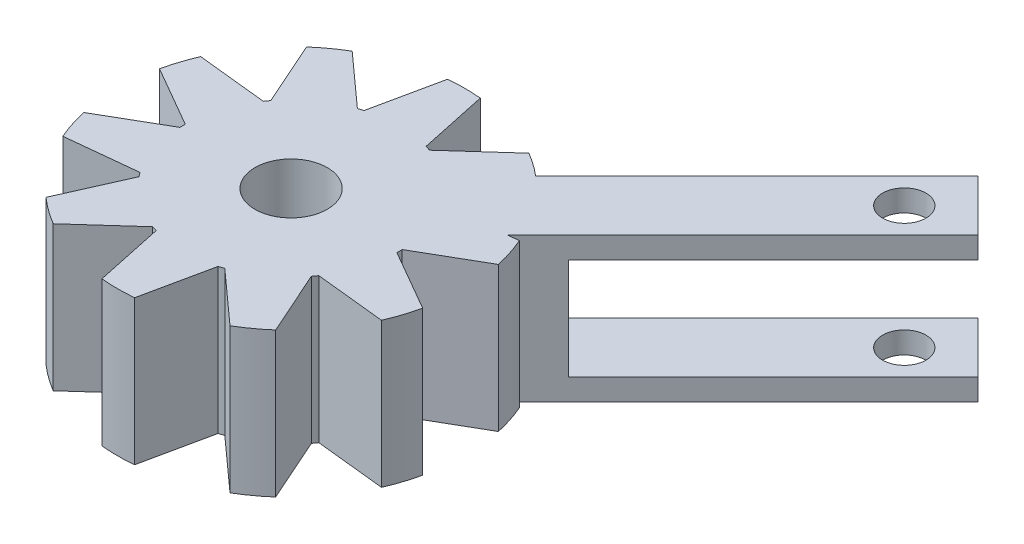
SolidWorks part; units mm, degrees
ref_plane "Front Plane" through (0, 0, 0) normal (0, 0, 1) x (1, 0, 0)
ref_plane "Top Plane" through (0, 0, 0) normal (0, 1, 0) x (1, 0, 0)
ref_plane "Right Plane" through (0, 0, 0) normal (1, 0, 0) x (0, 0, -1)
sketch "Sketch1" plane through (0, 0, 0) normal (0, 1, 0) x (1, 0, 0)
  line L0 (0, 0) -> (0, 13.746) construction
  line L1 (-1.57, 9.876) -> (1.57, 9.876)
  line L2 (1.1299, 11.9467) -> (2.1414, 7.1878)
  line L3 (-1.1299, 11.9467) -> (-2.1414, 7.1878)
  line L4 (7.9362, 9.001) -> (5.9573, 4.5564)
  line L5 (6.108, 10.3292) -> (2.4925, 7.0737)
  line L6 (11.7111, 2.6172) -> (7.4977, 0.1846)
  line L7 (11.0128, 4.7663) -> (6.1743, 4.2577)
  line L8 (11.0128, -4.7663) -> (6.1743, -4.2577)
  line L9 (11.7111, -2.6172) -> (7.4977, -0.1846)
  line L10 (6.108, -10.3292) -> (2.4925, -7.0737)
  line L11 (7.9362, -9.001) -> (5.9573, -4.5564)
  line L12 (-1.1299, -11.9467) -> (-2.1414, -7.1878)
  line L13 (1.1299, -11.9467) -> (2.1414, -7.1878)
  line L14 (-7.9362, -9.001) -> (-5.9573, -4.5564)
  line L15 (-6.108, -10.3292) -> (-2.4925, -7.0737)
  line L16 (-11.7111, -2.6172) -> (-7.4977, -0.1846)
  line L17 (-11.0128, -4.7663) -> (-6.1743, -4.2577)
  line L18 (-11.0128, 4.7663) -> (-6.1743, 4.2577)
  line L19 (-11.7111, 2.6172) -> (-7.4977, 0.1846)
  line L20 (-6.108, 10.3292) -> (-2.4925, 7.0737)
  line L21 (-7.9362, 9.001) -> (-5.9573, 4.5564)
  arc A0 (1.1299, 11.9467) -> (-1.1299, 11.9467) centre (0, 0) ccw
  arc A1 (-5.9573, 4.5564) -> (-6.1743, 4.2577) centre (0, 0) ccw
  circle A2 centre (0, 0) radius 10 construction
  arc A3 (7.9362, 9.001) -> (6.108, 10.3292) centre (0, 0) ccw
  arc A4 (11.7111, 2.6172) -> (11.0128, 4.7663) centre (0, 0) ccw
  arc A5 (11.0128, -4.7663) -> (11.7111, -2.6172) centre (0, 0) ccw
  arc A6 (6.108, -10.3292) -> (7.9362, -9.001) centre (0, 0) ccw
  arc A7 (-1.1299, -11.9467) -> (1.1299, -11.9467) centre (0, 0) ccw
  arc A8 (-7.9362, -9.001) -> (-6.108, -10.3292) centre (0, 0) ccw
  arc A9 (-11.7111, -2.6172) -> (-11.0128, -4.7663) centre (0, 0) ccw
  arc A10 (-11.0128, 4.7663) -> (-11.7111, 2.6172) centre (0, 0) ccw
  arc A11 (-6.108, 10.3292) -> (-7.9362, 9.001) centre (0, 0) ccw
  arc A12 (-7.4977, 0.1846) -> (-7.4977, -0.1846) centre (0, 0) ccw
  arc A13 (-6.1743, -4.2577) -> (-5.9573, -4.5564) centre (0, 0) ccw
  arc A14 (-2.4925, -7.0737) -> (-2.1414, -7.1878) centre (0, 0) ccw
  arc A15 (2.1414, -7.1878) -> (2.4925, -7.0737) centre (0, 0) ccw
  arc A16 (5.9573, -4.5564) -> (6.1743, -4.2577) centre (0, 0) ccw
  arc A17 (7.4977, -0.1846) -> (7.4977, 0.1846) centre (0, 0) ccw
  arc A18 (6.1743, 4.2577) -> (5.9573, 4.5564) centre (0, 0) ccw
  arc A19 (2.4925, 7.0737) -> (2.1414, 7.1878) centre (0, 0) ccw
  arc A20 (-2.1414, 7.1878) -> (-2.4925, 7.0737) centre (0, 0) ccw
  circle A21 centre (0, 0) radius 2.5
  point P50 (0, 0)
  dimension "D1" = 24
  dimension "D2" = 15
  dimension "D3" = 20
  dimension "D7" = 5
  dimension "D4" = 3.14
  dimension "D5" = 12
  dimension "D6" = 10
extrude "Boss-Extrude1" add sketch "Sketch1" along normal blind 10 contours L3 A20 L20 A11 L21 A1 L18 A10 L19 A12 L16 A9 L17 A13 L14 A8 L15 A14 L12 A7 L13 A15 L10 A6 L11 A16 L8 A5 L9 A17 L6 A4 L7 A18 L4 A3 L5 A19 L2 L1 A21 | L2 A0 L3 L1
sketch "Sketch2" plane through (0, 10, 0) normal (0, 1, 0) x (1, 0, 0)
  line L0 (1.7815, 3.2633) -> (22.9947, 24.4765)
  line L1 (22.9947, 24.4765) -> (26.5302, 20.9409)
  line L2 (26.5302, 20.9409) -> (5.317, -0.2723)
  line L3 (5.317, -0.2723) -> (1.7815, 3.2633)
  line L4 (3.5493, 1.4955) -> (29.0706, 27.0168) construction
  line L5 (0, 0) -> (27.6513, 0) construction
  dimension "D1" = 5
  dimension "D2" = 30
  dimension "D3" = 45
extrude "Boss-Extrude2" add sketch "Sketch2" against normal blind 10
sketch "Sketch3" plane through (0, 10, 0) normal (0, 1, 0) x (1, 0, 0)
  line L1 (10.2784, 4.6891) -> (26.5302, 20.9409) construction
  circle A0 centre (22.2152, 20.1615) radius 1.5
  dimension "D3" = 3
  dimension "D1" = 30
  dimension "D2" = 2.5
extrude "Cut-Extrude1" cut sketch "Sketch3" against normal blind 55
sketch "Sketch4" plane through (2.7946, 0, 2.7946) normal (0.7071, 0, 0.7071) x (0.7071, 0, -0.7071)
  line L0 (33.5672, 0) -> (33.5672, 10) construction
  line L1 (53.5672, 8.5) -> (13.5672, 8.5)
  line L2 (53.5672, 8.5) -> (53.5672, 1.5)
  line L3 (53.5672, 1.5) -> (13.5672, 1.5)
  line L4 (13.5672, 8.5) -> (13.5672, 1.5)
  line L5 (53.5672, 8.5) -> (13.5672, 1.5) construction
  line L6 (53.5672, 1.5) -> (13.5672, 8.5) construction
  point P0 (33.5672, 5)
  dimension "D1" = 20
  dimension "D2" = 7
extrude "Cut-Extrude2" cut sketch "Sketch4" against normal blind 10
